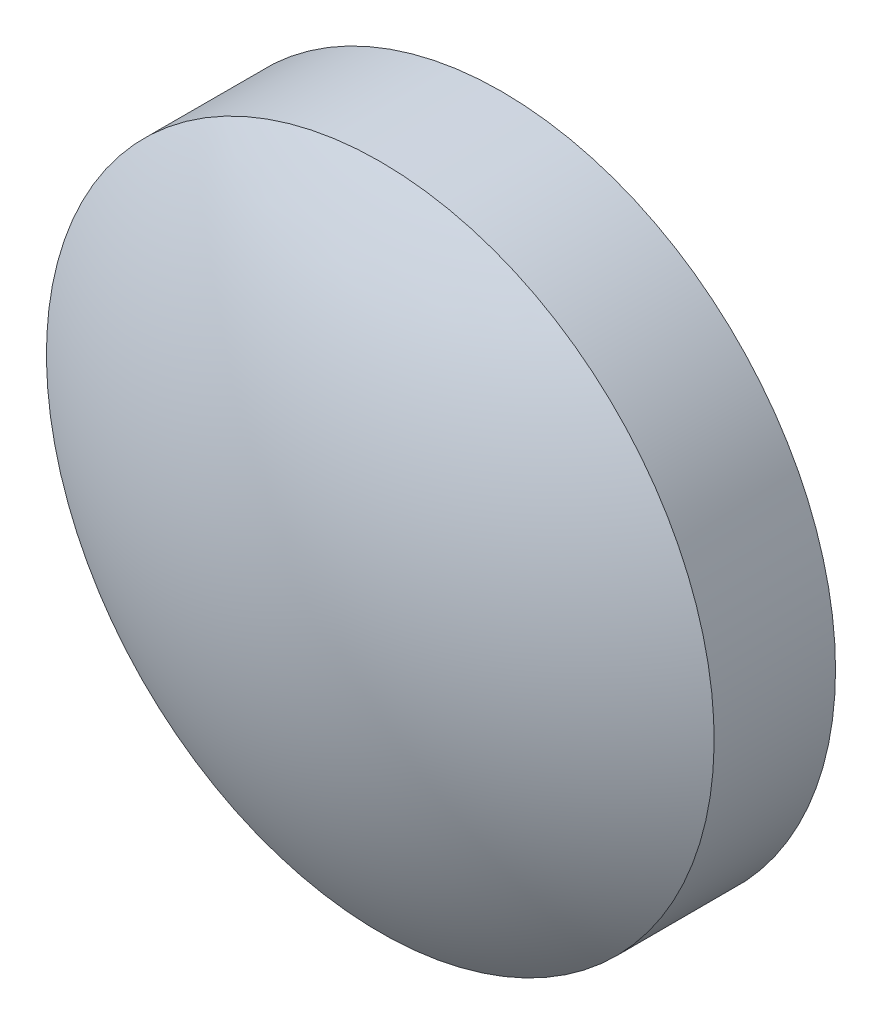
SolidWorks part; units mm, degrees
ref_plane "Front Plane" through (0, 0, 0) normal (0, 0, 1) x (1, 0, 0)
ref_plane "Top Plane" through (0, 0, 0) normal (0, 1, 0) x (1, 0, 0)
ref_plane "Right Plane" through (0, 0, 0) normal (1, 0, 0) x (0, 0, -1)
sketch "Sketch3" plane through (0, 0, 0) normal (1, 0, 0) x (0, 0, -1)
  line L0 (-1.3242, 0) -> (1.3242, 0)
  line L1 (0, 0) -> (0, 2.75)
  line L2 (-0.5, 2.75) -> (0.5, 2.75)
  line L3 (0, 0) -> (-3.6758, 0)
  arc A0 (1.3242, 0) -> (0.5, 2.75) centre (-3.6758, 0) ccw
  arc A1 (-1.3242, 0) -> (-0.5, 2.75) centre (3.6758, 0) cw
  dimension "D1" = 1.3242
  dimension "D2" = 2.75
  dimension "D3" = 0.5
  dimension "D4" = 3.6758
revolve "Revolve1" add sketch "Sketch3" angle 360 about L3
equation "\"T_edge\"= \"R\" * 0.2"
equation "\"R\"= \"gloabl_scale\" * 5mm"
equation "\"dT_c\"= \"R\" * ( 1 - sqr ( 1 - \"h\" ^ 2 / \"R\" ^ 2 ) )"
equation "\"h\"= 0.55 * \"R\""
equation "\"gloabl_scale\"= 1"
equation "\"x_sphere_origin\"= \"R\" - \"dT_c\" - \"T_edge\" / 2"
equation "\"T_c\"= \"T_edge\" + 2 * \"dT_c\""
equation "\"D1@Sketch3\"=\"T_c\" / 2"
equation "\"D2@Sketch3\"=\"h\""
equation "\"D3@Sketch3\"=\"T_edge\" / 2"
equation "\"D4@Sketch3\"=\"x_sphere_origin\""
